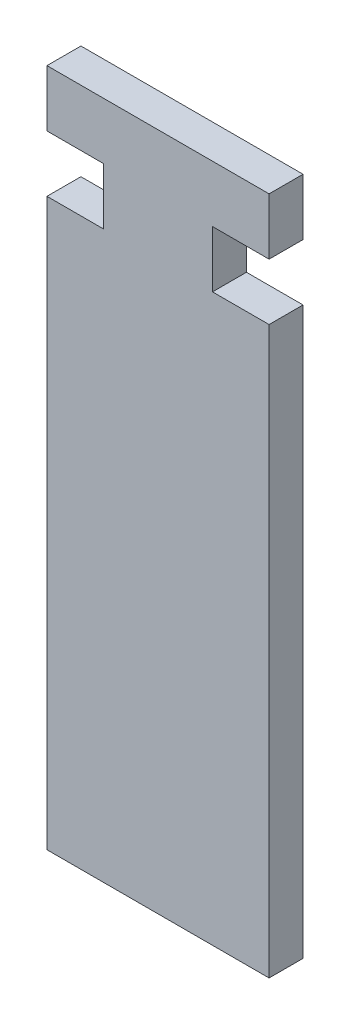
SolidWorks part; units mm, degrees
material "PBT General Purpose"
ref_plane "Front Plane" through (0, 0, 0) normal (0, 0, 1) x (1, 0, 0)
ref_plane "Top Plane" through (0, 0, 0) normal (0, 1, 0) x (1, 0, 0)
ref_plane "Right Plane" through (0, 0, 0) normal (1, 0, 0) x (0, 0, -1)
sketch "Sketch1" plane through (0, 0, 0) normal (0, 0, 1) x (1, 0, 0)
  line L0 (0, 0) -> (0, 4)
  line L1 (0, 4) -> (0.4, 4)
  line L2 (0.4, 4) -> (0.4, 4.4)
  line L3 (0.4, 4.4) -> (0, 4.4)
  line L4 (0, 4.4) -> (0, 4.8)
  line L5 (0, 4.8) -> (1.57, 4.8)
  line L6 (1.57, 4.8) -> (1.57, 4.4)
  line L7 (1.57, 4.4) -> (1.17, 4.4)
  line L8 (1.17, 4.4) -> (1.17, 4)
  line L9 (1.17, 4) -> (1.57, 4)
  line L10 (1.57, 4) -> (1.57, 0)
  line L11 (1.57, 0) -> (0, 0)
  dimension "D1" = 0.4
  dimension "D2" = 0.4
  dimension "D3" = 0.77
  dimension "D4" = 0.4
  dimension "D5" = 0.4
  dimension "D6" = 4
  dimension "D7" = 0.4
extrude "Boss-Extrude1" add sketch "Sketch1" along normal blind 0.24
